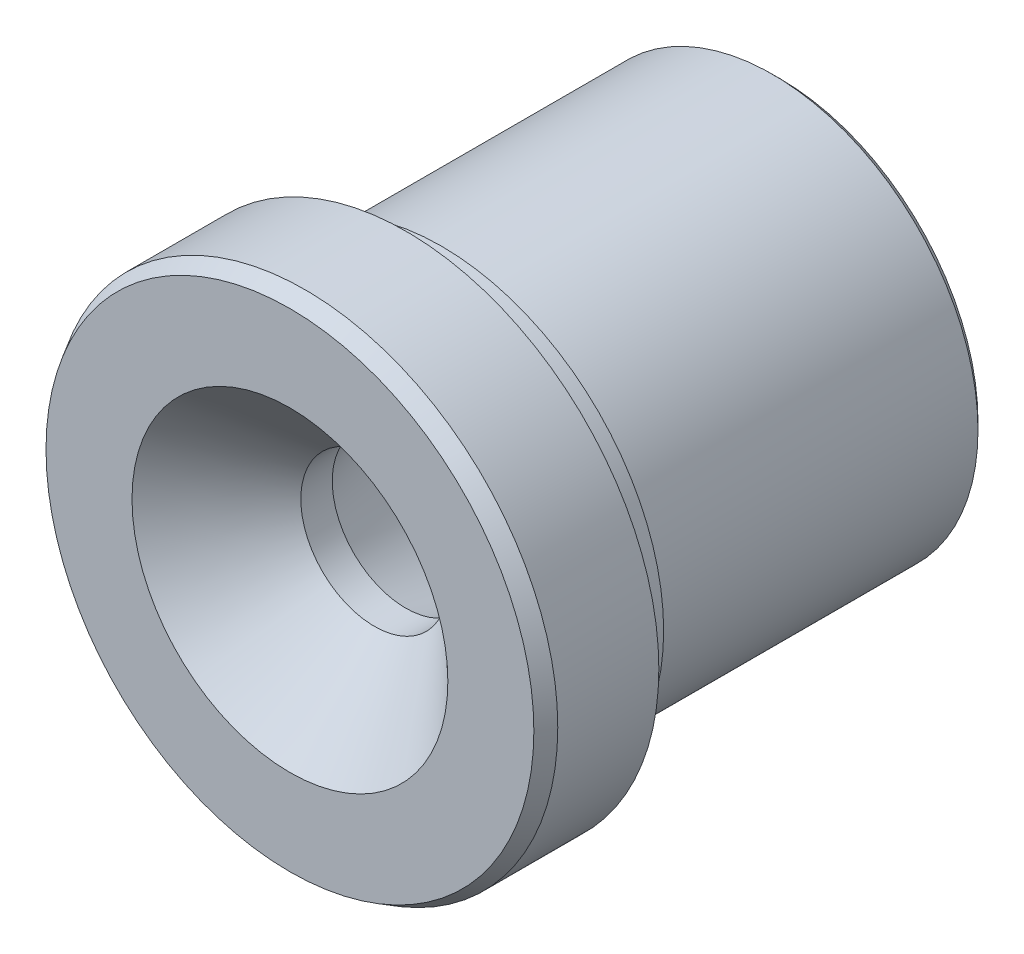
SolidWorks part; units mm, degrees
material "PF"
ref_plane "Front Plane" through (0, 0, 0) normal (0, 0, 1) x (1, 0, 0)
ref_plane "Top Plane" through (0, 0, 0) normal (0, 1, 0) x (1, 0, 0)
ref_plane "Right Plane" through (0, 0, 0) normal (1, 0, 0) x (0, 0, -1)
other "Configuration Table"
sketch "Sketch1" plane through (0, 0, 0) normal (1, 0, 0) x (0, 0, -1)
  line L0 (6.7166, 0) -> (19.724, 0) construction
  line L1 (24.638, -10.3251) -> (24.638, -8.7376)
  line L2 (24.638, -8.7376) -> (5.8214, -3.6957)
  line L3 (5.8214, -3.6957) -> (4.2418, -3.6957)
  line L4 (4.2418, -3.6957) -> (0, -7.9375)
  line L5 (0, -7.9375) -> (0, -12.7)
  line L6 (0, -12.7) -> (5.842, -12.7)
  line L7 (5.842, -12.7) -> (5.842, -11.1633)
  line L8 (5.842, -11.1633) -> (7.62, -11.1633)
  line L9 (7.62, -11.1633) -> (7.62, -10.3251)
  line L10 (7.62, -10.3251) -> (24.638, -10.3251)
  dimension "D1" = 25.4
  dimension "D2" = 24.638
  dimension "D3" = 15.875
  dimension "D4" = 17.4752
  dimension "D5" = 20.6502
  dimension "D6" = 22.3266
  dimension "D7" = 15
  dimension "D8" = 45
  dimension "D9" = 7.3914
  dimension "D10" = 5.842
  dimension "D11" = 7.62
revolve "Revolve1" add sketch "Sketch1" angle 360 about L0
chamfer "Chamfer1" distance 0.762 angle 30 1 edges at (12.7, 0, 0)
chamfer "Chamfer2" distance 0.381 angle 45 1 edges at (10.3251, 0, -24.638)
sketch "Sketch2" [suppressed] plane through (0, 0, 0) normal (0, 0, 1) x (1, 0, 0)
  point P0 (0, 0)
hole_wizard " (0.313) Diameter Hole0" [suppressed] positions "Sketch2" profile "Sketch3" hole size "5/16" standard "ANSI Inch"
sketch "Sketch3" plane through (0, 0, 0) normal (1, 0, 0) x (0, -1, 0)
  line L0 (0, 0) -> (0, 24.638)
  line L1 (0, 24.638) -> (3.9751, 24.638)
  line L2 (3.9751, 24.638) -> (3.9751, 0)
  line L5 (3.9751, 0) -> (0, 0)
  line L11 (0, -6.35) -> (0, 107.95) construction
  dimension "Thru Hole Dia." = 7.9502
  dimension "Thru Hole Depth" = 24.638
